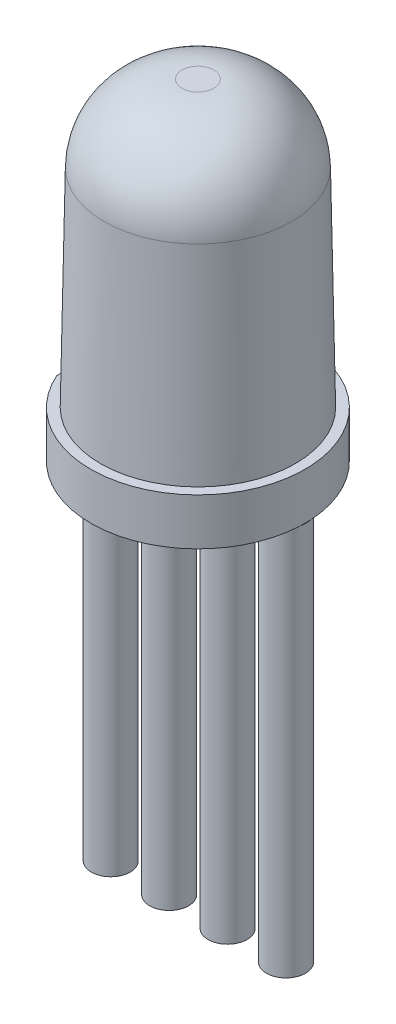
SolidWorks part; units mm, degrees
ref_plane "Front Plane" through (0, 0, 0) normal (0, 0, 1) x (1, 0, 0)
ref_plane "Top Plane" through (0, 0, 0) normal (0, 1, 0) x (1, 0, 0)
ref_plane "Right Plane" through (0, 0, 0) normal (1, 0, 0) x (0, 0, -1)
sketch "Sketch1" plane through (0, 0, 0) normal (0, 1, 0) x (1, 0, 0)
  circle A0 centre (0, 0) radius 2.75
  dimension "D1" = 5.5
extrude "Boss-Extrude1" add sketch "Sketch1" along normal blind 1.2
sketch "Sketch2" plane through (0, 1.2, 0) normal (0, 1, 0) x (1, 0, 0)
  circle A0 centre (0, 0) radius 2.5
  dimension "D1" = 5
extrude "Boss-Extrude2" add sketch "Sketch2" along normal blind 7.3 draft 1
fillet "Fillet1" radius 2 1 edges at (0, 8.5, 2.3726)
sketch "Sketch3" plane through (0, 1.2, 0) normal (0, 1, 0) x (1, 0, 0)
  line L1 (-5.4868, 8.1768) -> (-2.5183, 8.1768)
  line L2 (-5.4868, 8.1768) -> (-5.4868, -3.7704)
  line L3 (-5.4868, -3.7704) -> (-2.5183, -3.7704)
  line L4 (-2.5183, 8.1768) -> (-2.5183, -3.7704)
  line L5 (-5.4868, 8.1768) -> (-2.5183, -3.7704) construction
  line L6 (-5.4868, -3.7704) -> (-2.5183, 8.1768) construction
  point P0 (-4.0026, 2.2032)
extrude "Cut-Extrude1" cut sketch "Sketch3" against normal blind 7.3
sketch "Sketch4" plane through (0, 0, 0) normal (0, -1, 0) x (1, 0, 0)
  line L0 (-2.75, 0) -> (2.75, 0)
  arc A0 (-2.5183, -1.1048) -> (-2.5183, 1.1048) centre (0, 0) ccw construction
  circle A1 centre (-2.2381, 0) radius 0.5
  circle A2 centre (-0.7381, 0) radius 0.5
  circle A3 centre (0.7619, 0) radius 0.5
  circle A4 centre (2.2619, 0) radius 0.5
  point P7 (0, 0)
  arc M3 (-2.5183, -1.1048) -> (-2.5183, 1.1048) centre (0, 0) ccw
  line M4 (-2.5183, 1.1048) -> (-2.5183, -1.1048)
  dimension "D1" = 1
  dimension "D2" = 1
  dimension "D3" = 1
  dimension "D4" = 1
  dimension "D5" = 1.5
  dimension "D6" = 1.5
  dimension "D7" = 1.5
extrude "Boss-Extrude3" add sketch "Sketch4" along normal blind 10 separate body contours L0 A1 M4 | L0 A2 | L0 A3 | A4 L0 M3
